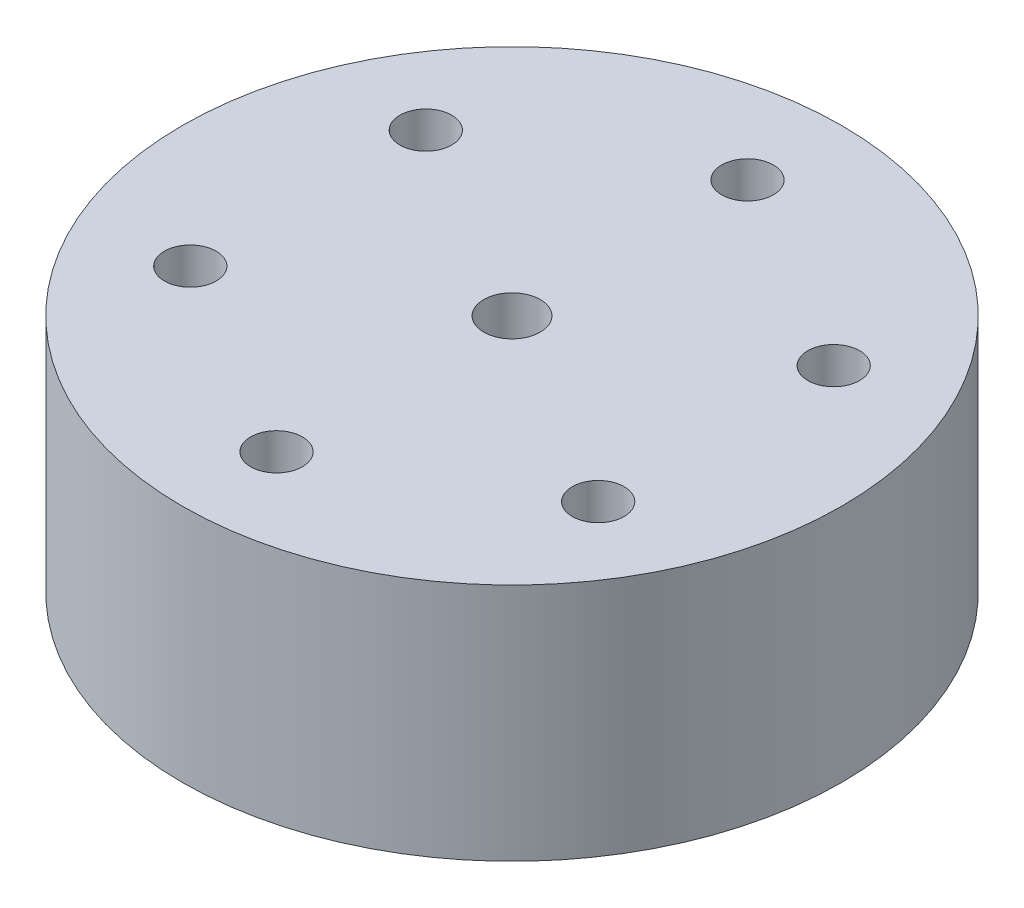
SolidWorks part; units mm, degrees
ref_plane "Front Plane" through (0, 0, 0) normal (0, 0, 1) x (1, 0, 0)
ref_plane "Top Plane" through (0, 0, 0) normal (0, 1, 0) x (1, 0, 0)
ref_plane "Right Plane" through (0, 0, 0) normal (1, 0, 0) x (0, 0, -1)
sketch "Sketch2" plane through (0, 0, 0) normal (0, 1, 0) x (1, 0, 0)
  circle A0 centre (0, 0) radius 35
  dimension "D1" = 70
extrude "Boss-Extrude1" add sketch "Sketch2" along normal blind 25.4
sketch "Sketch3" plane through (0, 25.4, 0) normal (0, 1, 0) x (1, 0, 0)
  line L0 (0, -3) -> (0, 2.5) construction
  arc A0 (-1.6583, 2.5) -> (1.6583, 2.5) centre (0, 0) ccw
  arc A1 (1.6583, 2.5) -> (-1.6583, 2.5) centre (0, 0) ccw
  dimension "D1" = 6
  dimension "D2" = 5.5
extrude "Cut-Extrude1" cut sketch "Sketch3" against normal through all
sketch "Sketch4" plane through (0, 0, -35) normal (0, 0, -1) x (-1, 0, 0)
  line L0 (0, 0) -> (0, 25.4) construction
  line L1 (-1.6583, 25.4) -> (1.6583, 25.4) construction
  circle A0 centre (0, 12.7) radius 1.5
  dimension "D1" = 3
sketch "Sketch5" plane through (0, 25.4, 0) normal (0, 1, 0) x (1, 0, 0)
  circle A0 centre (0, 0) radius 25 construction
  circle A1 centre (0, 25) radius 2.75
  circle A2 centre (21.6506, 12.5) radius 2.75
  circle A3 centre (21.6506, -12.5) radius 2.75
  circle A4 centre (0, -25) radius 2.75
  circle A5 centre (-21.6506, -12.5) radius 2.75
  circle A6 centre (-21.6506, 12.5) radius 2.75
  point P17 (0, 0)
  dimension "D1" = 50
  dimension "D2" = 5.5
  dimension "D3" = 6
extrude "Cut-Extrude3" cut sketch "Sketch5" against normal through all
